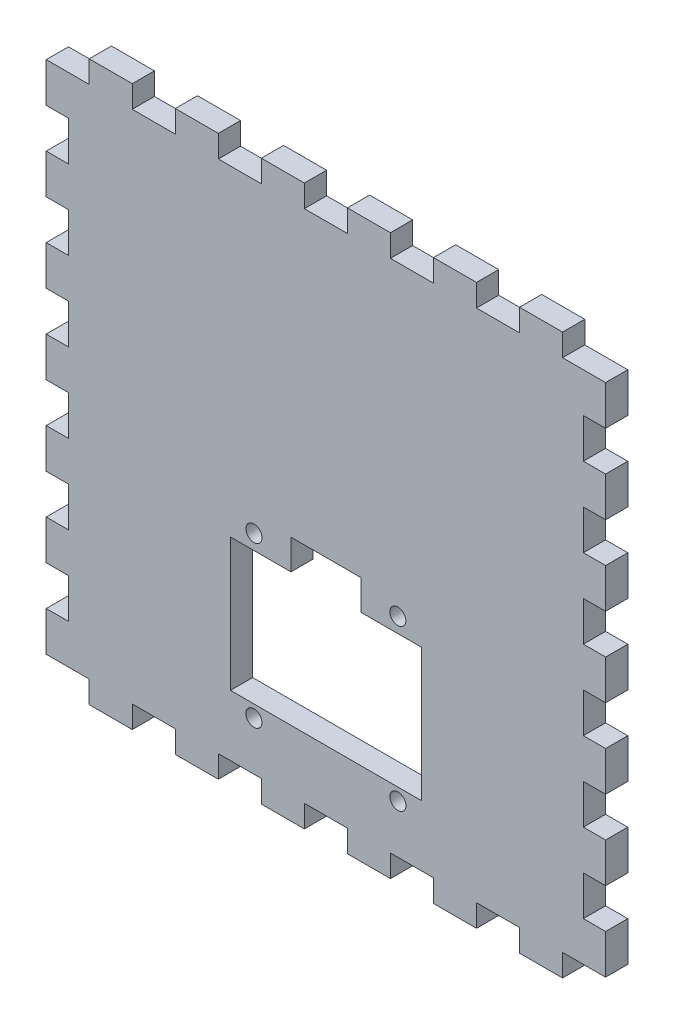
SolidWorks part; units mm, degrees
material "Acrylic (Medium-high impact)"
ref_plane "Front Plane" through (0, 0, 0) normal (0, 0, 1) x (1, 0, 0)
ref_plane "Top Plane" through (0, 0, 0) normal (0, 1, 0) x (1, 0, 0)
ref_plane "Right Plane" through (0, 0, 0) normal (1, 0, 0) x (0, 0, -1)
sketch "Sketch1" plane through (0, 0, 0) normal (0, 0, 1) x (1, 0, 0)
  line L1 (-40, -40) -> (40, -40)
  line L2 (-40, -40) -> (-40, 40)
  line L3 (-40, 40) -> (40, 40)
  line L4 (40, -40) -> (40, 40)
  line L5 (-40, -40) -> (40, 40) construction
  line L6 (-40, 40) -> (40, -40) construction
  point P0 (0, 0)
  dimension "D1" = 80
extrude "Boss-Extrude1" add sketch "Sketch1" along normal mid plane 3.175
sketch "Sketch2" plane through (0, 0, 1.5875) normal (0, 0, 1) x (1, 0, 0)
  line L0 (33.8462, -36.825) -> (40, -36.825)
  line L1 (40, 40) -> (-40, 40) construction
  line L2 (0, 0) -> (50000, 0) construction
  line L3 (40, -40) -> (40, 40) construction
  line L7 (-40, 36.825) -> (-33.8462, 36.825)
  line L8 (-33.8462, 36.825) -> (-33.8462, 40)
  line L9 (-33.8462, 40) -> (-27.6923, 40)
  line L10 (-21.5385, 40) -> (-15.3846, 40)
  line L11 (-21.5385, 36.825) -> (-21.5385, 40)
  line L12 (-27.6923, 36.825) -> (-21.5385, 36.825)
  line L13 (-27.6923, 40) -> (-27.6923, 36.825)
  line L14 (-9.2308, 40) -> (-3.0769, 40)
  line L15 (-9.2308, 36.825) -> (-9.2308, 40)
  line L16 (-15.3846, 36.825) -> (-9.2308, 36.825)
  line L17 (-15.3846, 40) -> (-15.3846, 36.825)
  line L18 (3.0769, 40) -> (9.2308, 40)
  line L19 (3.0769, 36.825) -> (3.0769, 40)
  line L20 (-3.0769, 36.825) -> (3.0769, 36.825)
  line L21 (-3.0769, 40) -> (-3.0769, 36.825)
  line L22 (15.3846, 40) -> (21.5385, 40)
  line L23 (15.3846, 36.825) -> (15.3846, 40)
  line L24 (9.2308, 36.825) -> (15.3846, 36.825)
  line L25 (9.2308, 40) -> (9.2308, 36.825)
  line L28 (21.5385, 36.825) -> (27.6923, 36.825)
  line L29 (21.5385, 40) -> (21.5385, 36.825)
  line L30 (27.6923, 40) -> (33.8462, 40) [skipped]
  line L57 (-40, 40) -> (-40, -40) construction
  line L58 (27.6923, 36.825) -> (27.6923, 40) [skipped]
  line L61 (27.6923, 36.825) -> (27.6923, 40)
  line L62 (27.6923, 40) -> (33.8462, 40)
  line L63 (33.8462, 40) -> (33.8462, 36.825)
  line L64 (33.8462, 36.825) -> (40, 36.825)
  line L65 (33.8462, -40) -> (33.8462, -36.825)
  line L66 (27.6923, -40) -> (33.8462, -40)
  line L67 (27.6923, -36.825) -> (27.6923, -40)
  line L68 (21.5385, -40) -> (21.5385, -36.825)
  line L69 (21.5385, -36.825) -> (27.6923, -36.825)
  line L70 (9.2308, -40) -> (9.2308, -36.825)
  line L71 (9.2308, -36.825) -> (15.3846, -36.825)
  line L72 (15.3846, -36.825) -> (15.3846, -40)
  line L73 (15.3846, -40) -> (21.5385, -40)
  line L74 (-3.0769, -40) -> (-3.0769, -36.825)
  line L75 (-3.0769, -36.825) -> (3.0769, -36.825)
  line L76 (3.0769, -36.825) -> (3.0769, -40)
  line L77 (3.0769, -40) -> (9.2308, -40)
  line L78 (-15.3846, -40) -> (-15.3846, -36.825)
  line L79 (-15.3846, -36.825) -> (-9.2308, -36.825)
  line L80 (-9.2308, -36.825) -> (-9.2308, -40)
  line L81 (-9.2308, -40) -> (-3.0769, -40)
  line L82 (-27.6923, -40) -> (-27.6923, -36.825)
  line L83 (-27.6923, -36.825) -> (-21.5385, -36.825)
  line L84 (-21.5385, -36.825) -> (-21.5385, -40)
  line L85 (-21.5385, -40) -> (-15.3846, -40)
  line L86 (-33.8462, -40) -> (-27.6923, -40)
  line L87 (-33.8462, -36.825) -> (-33.8462, -40)
  line L88 (-40, -36.825) -> (-33.8462, -36.825)
  line L91 (-40, 36.825) -> (-40, 31.1596)
  line L92 (-40, 31.1596) -> (-36.82, 31.1596)
  line L93 (-36.82, 31.1596) -> (-36.82, 25.4942)
  line L94 (-36.82, 25.4942) -> (-40, 25.4942)
  line L95 (-40, 25.4942) -> (-40, 19.8288)
  line L96 (-40, 19.8288) -> (-36.82, 19.8288)
  line L97 (-36.82, 19.8288) -> (-36.82, 14.1635)
  line L98 (-36.82, 14.1635) -> (-40, 14.1635)
  line L99 (-40, 14.1635) -> (-40, 8.4981)
  line L100 (-40, 8.4981) -> (-36.82, 8.4981)
  line L101 (-36.82, 8.4981) -> (-36.82, 2.8327)
  line L102 (-36.82, 2.8327) -> (-40, 2.8327)
  line L103 (-40, 2.8327) -> (-40, -2.8327)
  line L104 (-40, -2.8327) -> (-36.82, -2.8327)
  line L105 (-36.82, -2.8327) -> (-36.82, -8.4981)
  line L106 (-36.82, -8.4981) -> (-40, -8.4981)
  line L107 (-40, -8.4981) -> (-40, -14.1635)
  line L108 (-40, -14.1635) -> (-36.82, -14.1635)
  line L109 (-36.82, -14.1635) -> (-36.82, -19.8288)
  line L110 (-36.82, -19.8288) -> (-40, -19.8288)
  line L111 (-40, -19.8288) -> (-40, -25.4942)
  line L112 (-40, -25.4942) -> (-36.82, -25.4942)
  line L113 (-36.82, -25.4942) -> (-36.82, -31.1596)
  line L114 (-36.82, -31.1596) -> (-40, -31.1596)
  line L115 (-40, -31.1596) -> (-40, -36.825)
  line L116 (0, 0) -> (0, 50000) construction
  line L117 (40, -31.1596) -> (40, -36.825)
  line L118 (36.82, -31.1596) -> (40, -31.1596)
  line L119 (36.82, -25.4942) -> (36.82, -31.1596)
  line L120 (40, 36.825) -> (40, 31.1596)
  line L121 (40, -25.4942) -> (36.82, -25.4942)
  line L122 (40, -19.8288) -> (40, -25.4942)
  line L123 (36.82, -19.8288) -> (40, -19.8288)
  line L124 (36.82, -14.1635) -> (36.82, -19.8288)
  line L125 (40, -14.1635) -> (36.82, -14.1635)
  line L126 (40, -8.4981) -> (40, -14.1635)
  line L127 (36.82, -8.4981) -> (40, -8.4981)
  line L128 (36.82, -2.8327) -> (36.82, -8.4981)
  line L129 (40, -2.8327) -> (36.82, -2.8327)
  line L130 (40, 2.8327) -> (40, -2.8327)
  line L131 (36.82, 2.8327) -> (40, 2.8327)
  line L132 (36.82, 8.4981) -> (36.82, 2.8327)
  line L133 (40, 8.4981) -> (36.82, 8.4981)
  line L134 (40, 14.1635) -> (40, 8.4981)
  line L135 (36.82, 14.1635) -> (40, 14.1635)
  line L136 (36.82, 19.8288) -> (36.82, 14.1635)
  line L137 (40, 19.8288) -> (36.82, 19.8288)
  line L138 (40, 25.4942) -> (40, 19.8288)
  line L139 (36.82, 25.4942) -> (40, 25.4942)
  line L140 (36.82, 31.1596) -> (36.82, 25.4942)
  line L141 (40, 31.1596) -> (36.82, 31.1596)
  point P10 (40, 0)
  point P82 (0, 40)
  dimension "D1" = 3.175
  dimension "D3" = 3.18
  dimension "D5" = 6
  dimension "D6" = 6
extrude "Cut-Extrude2" cut sketch "Sketch2" against normal blind 10 flip side to cut
sketch "Sketch3" plane through (0, 0, 1.5875) normal (0, 0, 1) x (1, 0, 0)
  line L0 (0, 0) -> (0, 50000) construction
  line L1 (3.0769, 36.825) -> (-3.0769, 36.825) construction
  line L2 (-3.0769, -36.825) -> (3.0769, -36.825) construction
  line L3 (-13.65, -31.825) -> (13.65, -31.825)
  line L4 (-13.65, -31.825) -> (-13.65, -4.825)
  line L5 (-13.65, -4.825) -> (13.65, -4.825)
  line L6 (13.65, -31.825) -> (13.65, -4.825)
  line L7 (-13.65, -31.825) -> (13.65, -4.825) construction
  line L8 (-13.65, -4.825) -> (13.65, -31.825) construction
  line L9 (-5, -9.125) -> (-5, -4.825)
  line L10 (-13.65, -28.125) -> (13.65, -28.125)
  line L11 (-13.65, -28.125) -> (-13.65, -9.125)
  line L12 (-13.65, -9.125) -> (-5, -9.125)
  line L13 (13.65, -28.125) -> (13.65, -9.125)
  line L14 (5, -9.125) -> (5, -4.825)
  line L15 (5, -9.125) -> (13.65, -9.125)
  circle A0 centre (-10.2846, -6.975) radius 1.15
  circle A1 centre (10.2846, -6.975) radius 1.15
  circle A2 centre (-10.3, -29.875) radius 1.15
  circle A3 centre (10.3, -29.875) radius 1.15
  point P5 (0, 36.825)
  point P6 (0, -18.325)
  dimension "D6" = 2.3
  dimension "D9" = 2.3
  dimension "D1" = 27
  dimension "D2" = 27.3
  dimension "D3" = 5
  dimension "D4" = 19
  dimension "D5" = 22.7
  dimension "D7" = 3.3654
  dimension "D8" = 2.15
  dimension "D10" = 3.35
  dimension "D11" = 1.95
  dimension "D12" = 5
extrude "Cut-Extrude3" cut sketch "Sketch3" against normal through all contours L12 L4 L10 L6 | A0 | A1 | A2 | A3
